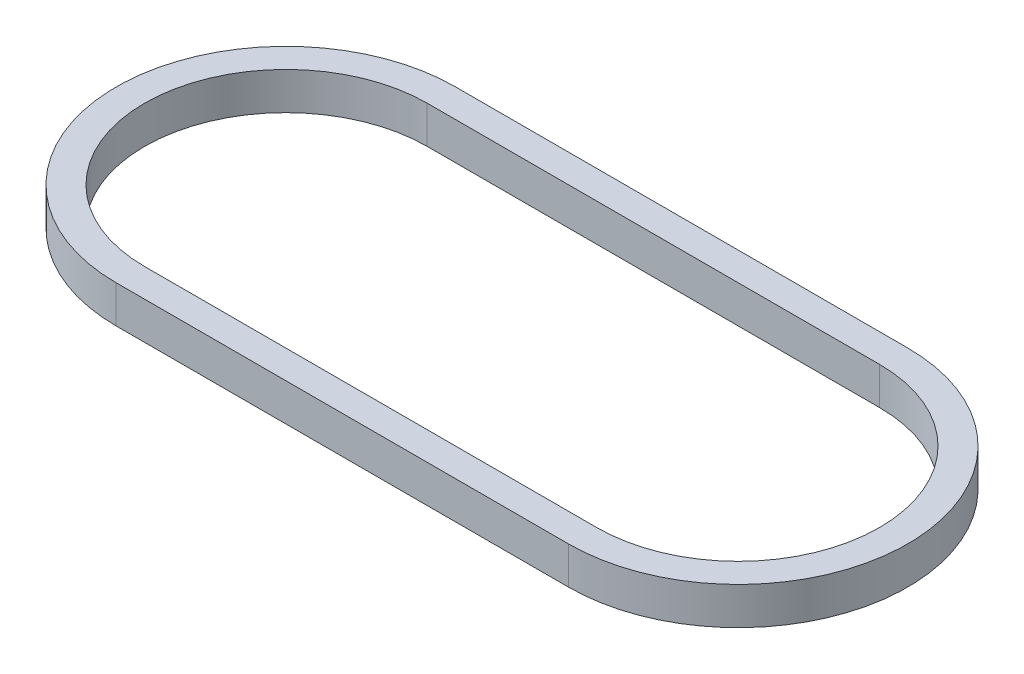
SolidWorks part; units mm, degrees
material "6061 Alloy"
ref_plane "Front Plane" through (0, 0, 0) normal (0, 0, 1) x (1, 0, 0)
ref_plane "Top Plane" through (0, 0, 0) normal (0, 1, 0) x (1, 0, 0)
ref_plane "Right Plane" through (0, 0, 0) normal (1, 0, 0) x (0, 0, -1)
sketch "Sketch1" plane through (0, 0, 0) normal (0, 1, 0) x (1, 0, 0)
  line L0 (-47.1, 0) -> (47.1, 0) construction
  line L1 (-47.1, 0) -> (47.1, 0) construction
  line L3 (-47.1, -35.3387) -> (47.1, -35.3387)
  line L4 (-47.1, 0) -> (47.1, 0) construction
  line L6 (-47.1, -29.4459) -> (47.1, -29.4459)
  line L7 (-47.1, 29.4459) -> (-47.1, 35.3387) construction
  line L8 (0, 0) -> (0, 18) construction
  line L9 (-47.1, 35.3387) -> (47.1, 35.3387)
  line L14 (-47.1, 29.4459) -> (47.1, 29.4459)
  arc A0 (-47.1, 35.3387) -> (-47.1, -35.3387) centre (-47.1, 0) ccw
  arc A1 (47.1, -35.3387) -> (47.1, 35.3387) centre (47.1, 0) ccw
  arc A2 (-47.1, 29.4459) -> (-47.1, -29.4459) centre (-47.1, 0) ccw
  arc A3 (47.1, -29.4459) -> (47.1, 29.4459) centre (47.1, 0) ccw
  point P0 (0, 0)
  point P4 (0, 0)
  point P10 (0, 0)
  point P18 (-47.1, 32.3923)
  dimension "D2" = 32.3923
  dimension "D3" = 5.8928
  dimension "D1" = 94.2
  dimension "D5" = 18
extrude "Boss-Extrude1" add sketch "Sketch1" along normal blind 7.7978
